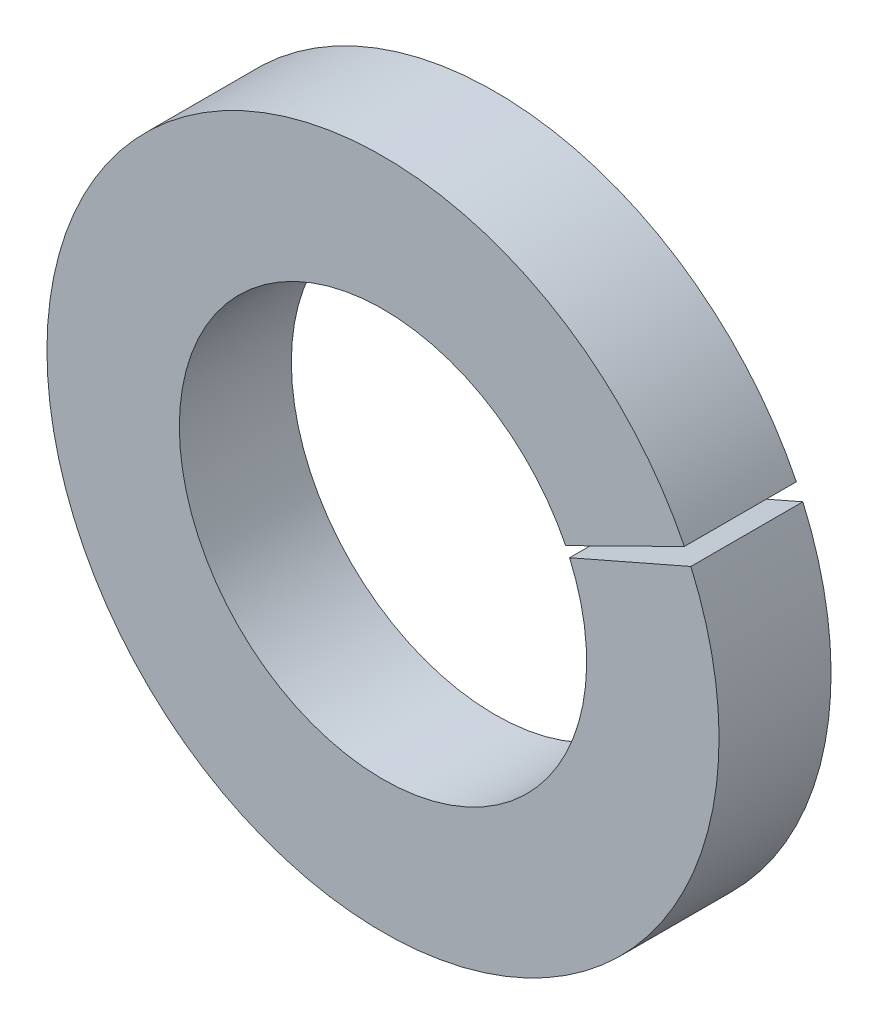
SolidWorks part; units mm, degrees
ref_plane "前视基准面" through (0, 0, 0) normal (0, 0, 1) x (1, 0, 0)
ref_plane "上视基准面" through (0, 0, 0) normal (0, 1, 0) x (1, 0, 0)
ref_plane "右视基准面" through (0, 0, 0) normal (1, 0, 0) x (0, 0, -1)
sketch "草图1" plane through (0, 0, 0) normal (0, 0, 1) x (1, 0, 0)
  circle A0 centre (0, 0) radius 1.65
  circle A1 centre (0, 0) radius 1
  dimension "D1" = 2
  dimension "D2" = 3.3
extrude "凸台-拉伸1" add sketch "草图1" along normal blind 0.55
sketch "草图2" plane through (0, 0, 0.55) normal (0, 0, 1) x (1, 0, 0)
  line L0 (0, 0) -> (4.8125, 2.3756)
  line L1 (4.8125, 2.3756) -> (4.8125, 2.1059)
  line L2 (4.8125, 2.1059) -> (0, 0)
extrude "切除-拉伸1" cut sketch "草图2" against normal blind 10
